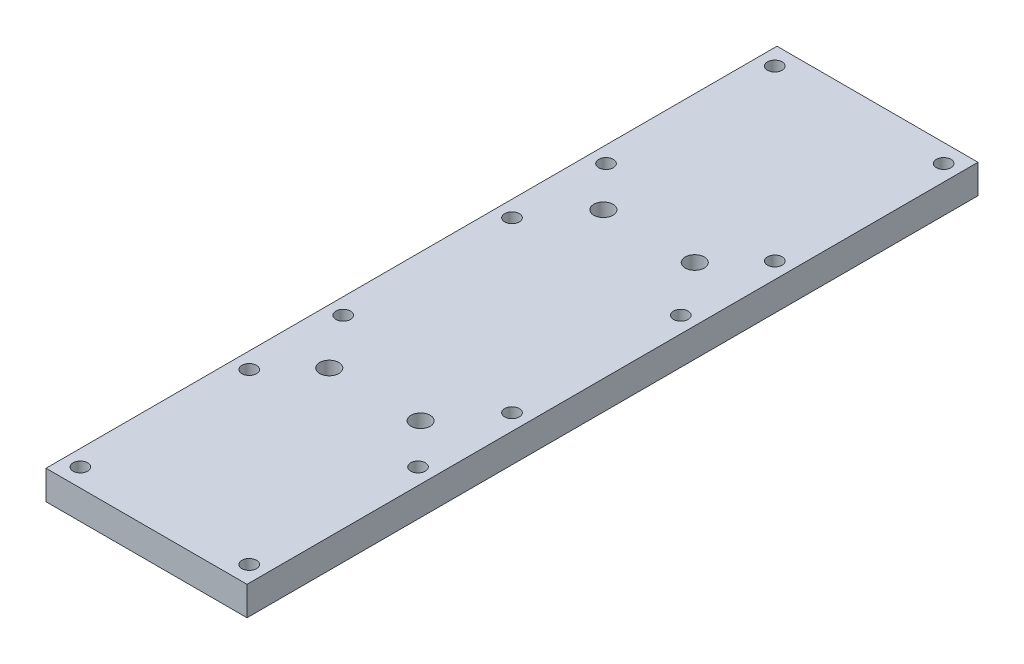
SolidWorks part; units mm, degrees
ref_plane "Front Plane" through (0, 0, 0) normal (0, 0, 1) x (1, 0, 0)
ref_plane "Top Plane" through (0, 0, 0) normal (0, 1, 0) x (1, 0, 0)
ref_plane "Right Plane" through (0, 0, 0) normal (1, 0, 0) x (0, 0, -1)
sketch "Sketch1" plane through (0, 0, 0) normal (0, 1, 0) x (1, 0, 0)
  line L1 (-22, 80) -> (22, 80)
  line L2 (-22, 80) -> (-22, -80)
  line L3 (-22, -80) -> (22, -80)
  line L4 (22, 80) -> (22, -80)
  line L5 (-22, 80) -> (22, -80) construction
  line L6 (-22, -80) -> (22, 80) construction
  point P0 (0, 0)
  dimension "D1" = 160
  dimension "D2" = 44
extrude "Boss-Extrude1" add sketch "Sketch1" along normal blind 6.35
sketch "Sketch2" plane through (0, 6.35, 0) normal (0, 1, 0) x (1, 0, 0)
  line L0 (-18.475, 39.05) -> (18.475, 39.05) construction
  line L1 (-18.475, -18.475) -> (18.475, -18.475) construction
  line L2 (-18.475, -18.475) -> (-18.475, 18.475) construction
  line L3 (-18.475, 18.475) -> (18.475, 18.475) construction
  line L4 (18.475, -18.475) -> (18.475, 18.475) construction
  line L5 (-18.475, -18.475) -> (18.475, 18.475) construction
  line L6 (-18.475, 18.475) -> (18.475, -18.475) construction
  line L7 (-18.475, 39.05) -> (-18.475, 76) construction
  line L8 (-18.475, 76) -> (18.475, 76) construction
  line L9 (18.475, 39.05) -> (18.475, 76) construction
  line L10 (-18.475, 39.05) -> (18.475, 76) construction
  line L11 (-18.475, 76) -> (18.475, 39.05) construction
  line L12 (-18.475, -76) -> (18.475, -76) construction
  line L13 (-18.475, -76) -> (-18.475, -39.05) construction
  line L14 (-18.475, -39.05) -> (18.475, -39.05) construction
  line L15 (18.475, -76) -> (18.475, -39.05) construction
  line L16 (-18.475, -76) -> (18.475, -39.05) construction
  line L17 (-18.475, -39.05) -> (18.475, -76) construction
  line L18 (0, 57.525) -> (0, -57.525) construction
  line L19 (0, -76) -> (0, -80) construction
  line L20 (-22, -80) -> (22, -80) construction
  line L21 (0, 76) -> (0, 80) construction
  line L22 (22, 80) -> (-22, 80) construction
  circle A0 centre (-18.475, 18.475) radius 1.6
  circle A1 centre (-18.475, -18.475) radius 1.6
  circle A2 centre (18.475, -18.475) radius 1.6
  circle A3 centre (18.475, 18.475) radius 1.6
  circle A4 centre (-18.475, 76) radius 1.6
  circle A5 centre (-18.475, 39.05) radius 1.6
  circle A6 centre (18.475, 39.05) radius 1.6
  circle A7 centre (18.475, 76) radius 1.6
  circle A8 centre (-18.475, -39.05) radius 1.6
  circle A9 centre (-18.475, -76) radius 1.6
  circle A10 centre (18.475, -76) radius 1.6
  circle A11 centre (18.475, -39.05) radius 1.6
  point P0 (0, 0)
  point P10 (0, 57.525)
  point P19 (0, -57.525)
  dimension "D1" = 3.2
  dimension "D2" = 36.95
  dimension "D3" = 36.95
  dimension "D4" = 36.95
  dimension "D5" = 4
extrude "Cut-Extrude1" cut sketch "Sketch2" against normal through all
sketch "Sketch3" plane through (0, 6.35, 0) normal (0, 1, 0) x (1, 0, 0)
  line L1 (-10, -30) -> (10, -30) construction
  line L2 (-10, -30) -> (-10, 30) construction
  line L3 (-10, 30) -> (10, 30) construction
  line L4 (10, -30) -> (10, 30) construction
  line L5 (-10, -30) -> (10, 30) construction
  line L6 (-10, 30) -> (10, -30) construction
  circle A0 centre (-10, 30) radius 2.1
  circle A1 centre (10, 30) radius 2.1
  circle A2 centre (-10, -30) radius 2.1
  circle A3 centre (10, -30) radius 2.1
  point P0 (0, 0)
  dimension "D3" = 4.2
  dimension "D1" = 20
  dimension "D2" = 60
extrude "Cut-Extrude2" cut sketch "Sketch3" against normal through all
